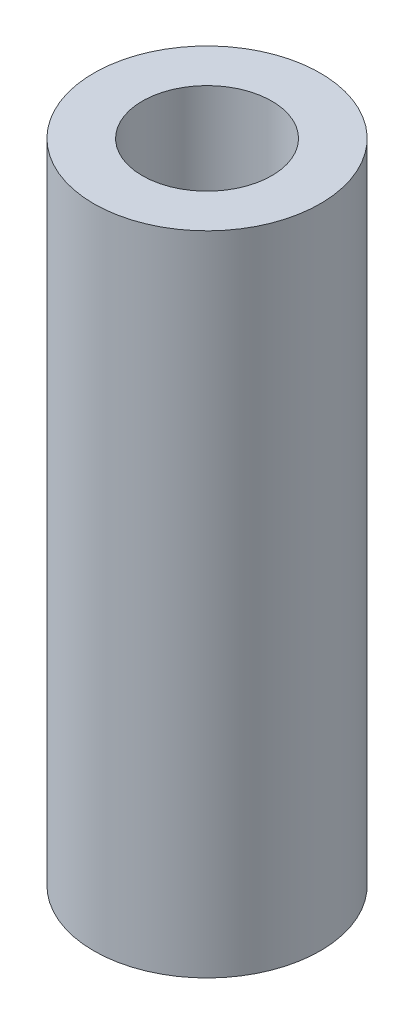
SolidWorks part; units mm, degrees
material "1060 合金"
ref_plane "前视基准面" through (0, 0, 0) normal (0, 0, 1) x (1, 0, 0)
ref_plane "上视基准面" through (0, 0, 0) normal (0, 1, 0) x (1, 0, 0)
ref_plane "右视基准面" through (0, 0, 0) normal (1, 0, 0) x (0, 0, -1)
sketch "草图1" plane through (0, 0, 0) normal (0, 1, 0) x (1, 0, 0)
  circle A0 centre (0, 0) radius 2
  circle A1 centre (0, 0) radius 3.5
  dimension "D1" = 4
  dimension "D2" = 7
extrude "凸台-拉伸1" add sketch "草图1" along normal blind 20
